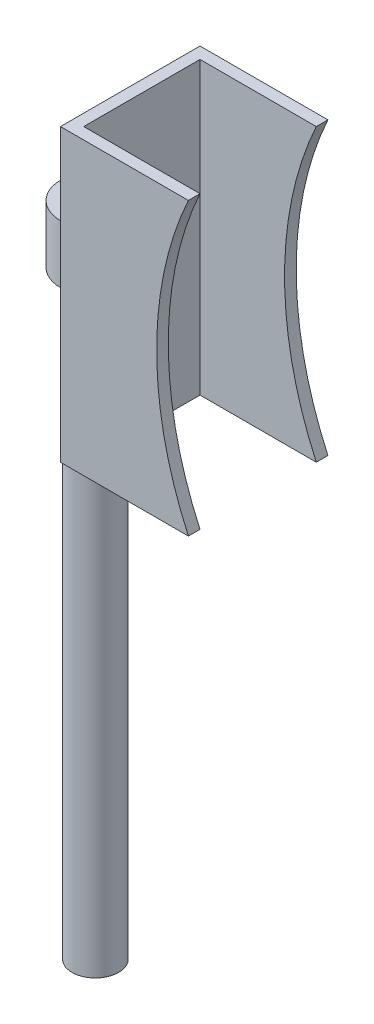
SolidWorks part; units mm, degrees
ref_plane "Front Plane" through (0, 0, 0) normal (0, 0, 1) x (1, 0, 0)
ref_plane "Top Plane" through (0, 0, 0) normal (0, 1, 0) x (1, 0, 0)
ref_plane "Right Plane" through (0, 0, 0) normal (1, 0, 0) x (0, 0, -1)
sketch "Sketch1" plane through (0, 0, 0) normal (0, 1, 0) x (1, 0, 0)
  line L0 (0, 0) -> (0, 20)
  line L1 (0, 20) -> (20, 20)
  line L2 (0, 0) -> (20, 0)
  line L3 (-2, -2) -> (20, -2)
  line L4 (-2, -2) -> (-2, 22)
  line L5 (-2, 22) -> (20, 22)
  line L6 (20, 20) -> (20, 22)
  line L7 (20, 0) -> (20, -2)
  dimension "D1" = 20
  dimension "D2" = 20
  dimension "D3" = 20
  dimension "D4" = 2
extrude "Boss-Extrude1" add sketch "Sketch1" along normal blind 50
sketch "Sketch3" plane through (0, 0, -22) normal (0, 0, -1) x (-1, 0, 0)
  circle A0 centre (-74.5436, 25) radius 60
  dimension "D1" = 120
extrude "Cut-Extrude1" cut sketch "Sketch3" against normal through all both and the other way through all
sketch "Sketch4" plane through (0, 50, 0) normal (0, 1, 0) x (1, 0, 0)
  line L0 (-2, 10) -> (-11.6031, 10) construction
  line L1 (-2, 22) -> (-2, -2) construction
  circle A0 centre (-8, 10) radius 4
  circle A1 centre (-8, 10) radius 6
  dimension "D1" = 8
  dimension "D2" = 2
extrude "Boss-Extrude2" add sketch "Sketch4" along normal blind 10 from offset 30 separate body offset against normal yes
sketch "Sketch5" plane through (0, 20, 0) normal (0, -1, 0) x (1, 0, 0)
  circle A0 centre (-8, -10) radius 4
extrude "Boss-Extrude3" add sketch "Sketch5" along normal blind 123 from offset 20
